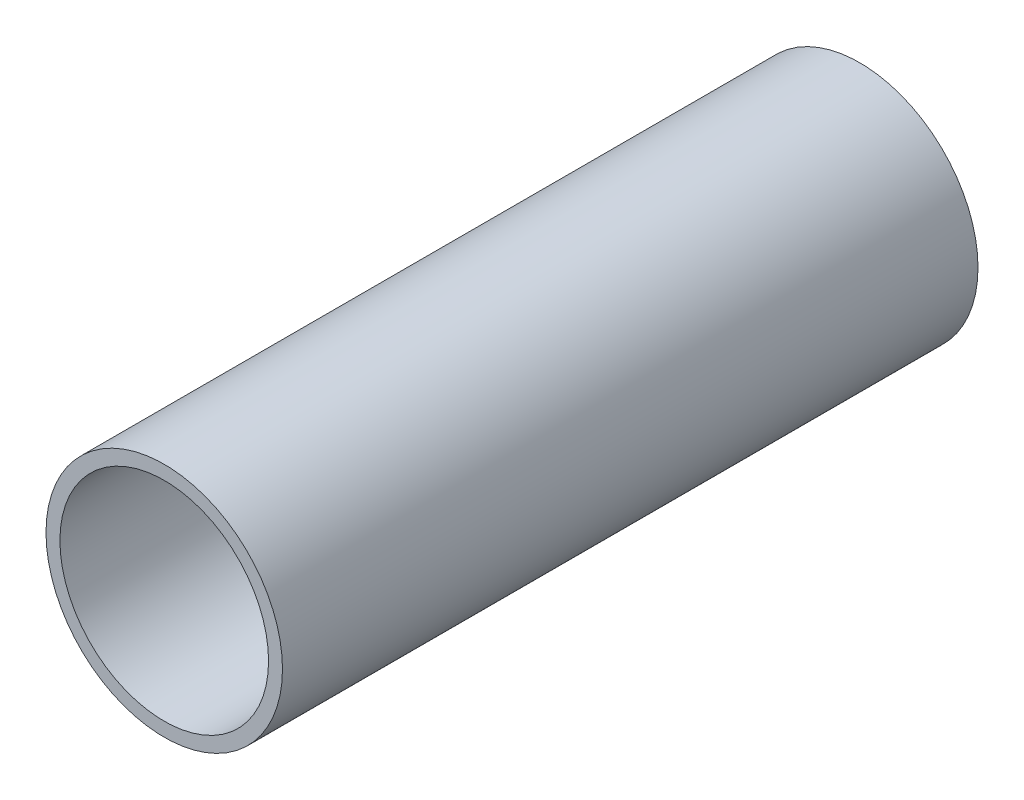
SolidWorks part; units mm, degrees
material "Copper"
ref_plane "Front Plane" through (0, 0, 0) normal (0, 0, 1) x (1, 0, 0)
ref_plane "Top Plane" through (0, 0, 0) normal (0, 1, 0) x (1, 0, 0)
ref_plane "Right Plane" through (0, 0, 0) normal (1, 0, 0) x (0, 0, -1)
sketch "Sketch2" plane through (0, 0, 0) normal (0, 0, 1) x (1, 0, 0)
  circle A0 centre (0, 0) radius 8.5
  dimension "D1" = 17
extrude "Boss-Extrude1" add sketch "Sketch2" along normal blind 50
sketch "Sketch3" plane through (0, 0, 50) normal (0, 0, 1) x (1, 0, 0)
  circle A0 centre (0, 0) radius 7.5
  dimension "D1" = 15
extrude "Cut-Extrude1" cut sketch "Sketch3" against normal up to next
